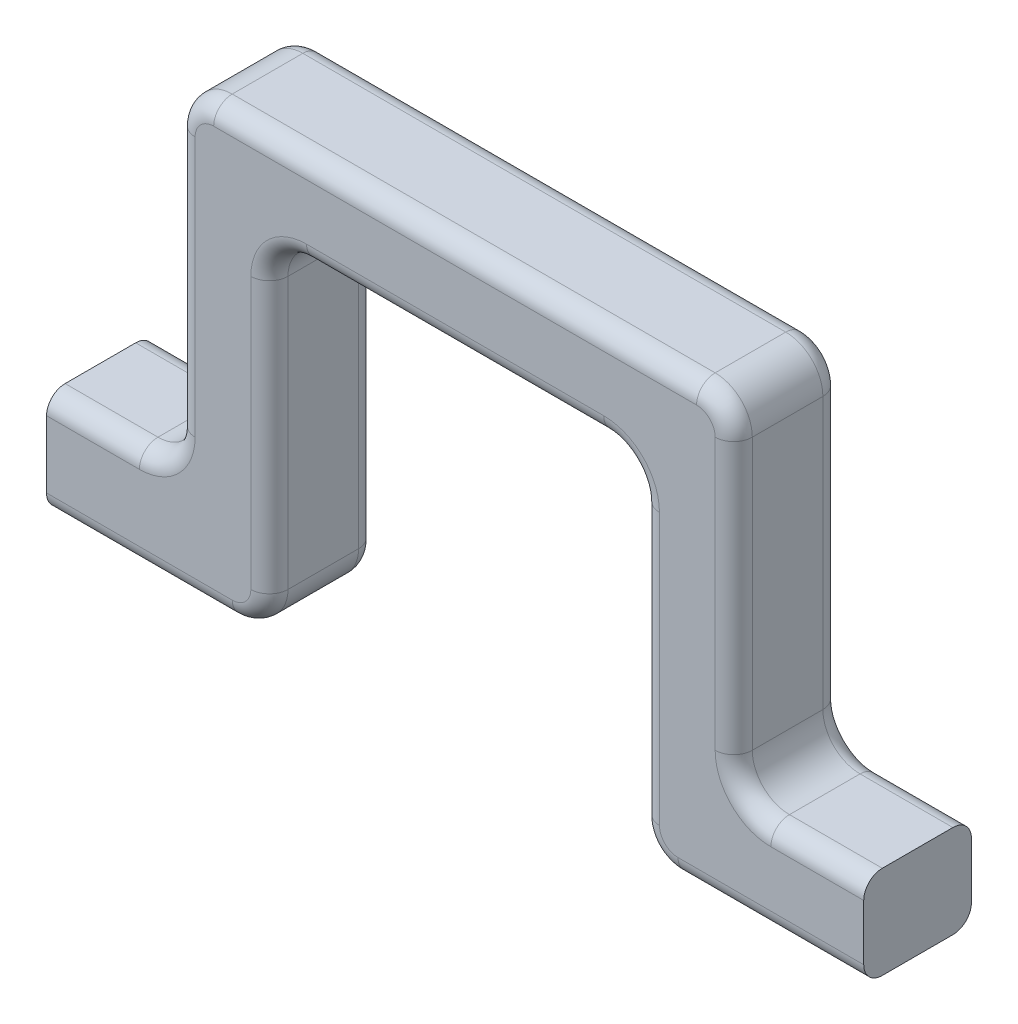
SolidWorks part; units mm, degrees
ref_plane "Front Plane" through (0, 0, 0) normal (0, 0, 1) x (1, 0, 0)
ref_plane "Top Plane" through (0, 0, 0) normal (0, 1, 0) x (1, 0, 0)
ref_plane "Right Plane" through (0, 0, 0) normal (1, 0, 0) x (0, 0, -1)
sketch "Sketch3" plane through (0, 0, 0) normal (1, 0, 0) x (0, 0, -1)
  line L1 (14.5, 14) -> (-14.5, 14)
  line L2 (14.5, 14) -> (14.5, -14)
  line L3 (14.5, -14) -> (-14.5, -14)
  line L4 (-14.5, 14) -> (-14.5, -14)
  line L5 (14.5, 14) -> (-14.5, -14) construction
  line L6 (14.5, -14) -> (-14.5, 14) construction
  point P0 (0, 0)
  dimension "D1" = 29
  dimension "D2" = 28
extrude "Boss-Extrude2" add sketch "Sketch3" along normal blind 60
sketch "Sketch4" plane through (0, 14, 0) normal (0, 1, 0) x (1, 0, 0)
  line L0 (60, 14.5) -> (60, -14.5) construction
  line L1 (35, 14.5) -> (60, 14.5)
  line L2 (35, 14.5) -> (35, -14.5)
  line L3 (35, -14.5) -> (60, -14.5)
  line L4 (60, 14.5) -> (60, -14.5)
  line L5 (35, 14.5) -> (60, -14.5) construction
  line L6 (35, -14.5) -> (60, 14.5) construction
  line L7 (60, 14.5) -> (0, 14.5) construction
  point P0 (47.5, 0)
  dimension "D1" = 29
  dimension "D2" = 0
  dimension "10" = 25
extrude "Boss-Extrude3" add sketch "Sketch4" along normal blind 90
sketch "Sketch5" plane through (60, 0, 0) normal (1, 0, 0) x (0, 0, -1)
  line L0 (-14.5, 104) -> (-14.5, -14) construction
  line L1 (-14.5, 104) -> (14.5, 104)
  line L2 (-14.5, 104) -> (-14.5, 79)
  line L3 (-14.5, 79) -> (14.5, 79)
  line L4 (14.5, 104) -> (14.5, 79)
  line L5 (-14.5, 104) -> (14.5, 104) construction
  line L6 (14.5, -14) -> (14.5, 104) construction
  dimension "D1" = 25
extrude "Boss-Extrude4" add sketch "Sketch5" along normal blind 125
sketch "Sketch7" plane through (0, 79, 0) normal (0, -1, 0) x (1, 0, 0)
  line L0 (185, -14.5) -> (60, -14.5) construction
  line L1 (185, 14.5) -> (160, 14.5)
  line L2 (185, 14.5) -> (185, -14.5)
  line L3 (185, -14.5) -> (160, -14.5)
  line L4 (160, 14.5) -> (160, -14.5)
  dimension "D1" = 25
extrude "Boss-Extrude5" add sketch "Sketch7" along normal blind 93
sketch "Sketch8" plane through (185, 0, 0) normal (1, 0, 0) x (0, 0, -1)
  line L0 (-14.5, 104) -> (-14.5, -14) construction
  line L1 (14.5, -14) -> (-14.5, -14)
  line L2 (14.5, -14) -> (14.5, 11)
  line L3 (14.5, 11) -> (-14.5, 11)
  line L4 (-14.5, -14) -> (-14.5, 11)
  dimension "D1" = 25
extrude "Boss-Extrude6" add sketch "Sketch8" along normal blind 35
fillet "Fillet1" radius 10 5 edges at (160, 79, 0) (35, 14, 0) (35, 104, 0) (185, 104, 0) (185, 11, 0)
fillet "Fillet2" radius 10 3 edges at (60, -14, 0) (160, -14, 0) (60, 79, 0)
fillet "Fillet3" radius 5 36 edges at (25, -14, -14.5) (57.0711, -11.0711, -14.5) (60, 32.5, -14.5) (62.9289, 76.0711, -14.5) (110, 79, -14.5) (157.0711, 76.0711, -14.5) (160, 32.5, -14.5) (162.9289, -11.0711, -14.5) (25, -14, 14.5) (57.0711, -11.0711, 14.5) (60, 32.5, 14.5) (62.9289, 76.0711, 14.5) (110, 79, 14.5) (157.0711, 76.0711, 14.5) (160, 32.5, 14.5) (162.9289, -11.0711, 14.5) (12.5, 14, -14.5) (32.0711, 16.9289, -14.5) (35, 59, -14.5) (37.9289, 101.0711, -14.5) (110, 104, -14.5) (182.0711, 101.0711, -14.5) (185, 57.5, -14.5) (187.9289, 13.9289, -14.5) (12.5, 14, 14.5) (32.0711, 16.9289, 14.5) (35, 59, 14.5) (37.9289, 101.0711, 14.5) (110, 104, 14.5) (182.0711, 101.0711, 14.5) (185, 57.5, 14.5) (187.9289, 13.9289, 14.5) (195, -14, -14.5) (195, -14, 14.5) (207.5, 11, -14.5) (207.5, 11, 14.5)
